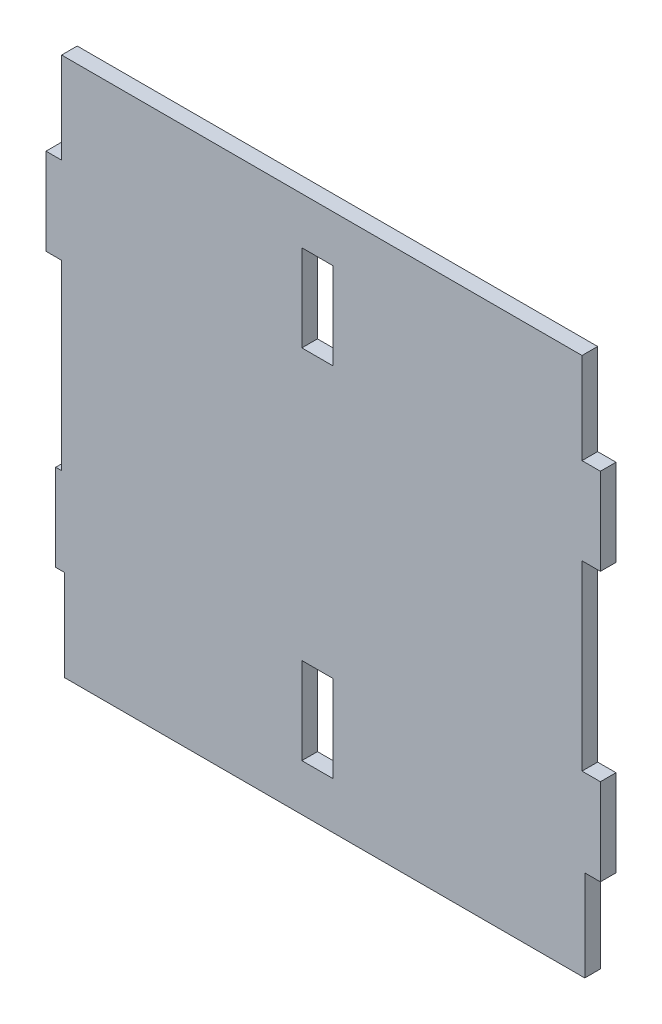
SolidWorks part; units mm, degrees
ref_plane "Front Plane" through (0, 0, 0) normal (0, 0, 1) x (1, 0, 0)
ref_plane "Top Plane" through (0, 0, 0) normal (0, 1, 0) x (1, 0, 0)
ref_plane "Right Plane" through (0, 0, 0) normal (1, 0, 0) x (0, 0, -1)
sketch "Sketch1" plane through (0, 0, 0) normal (0, 0, 1) x (1, 0, 0)
  line L0 (0, 0) -> (0, -105)
  line L6 (0, -205) -> (0, -415)
  line L7 (-18, -105) -> (0, -105)
  line L8 (-18, -105) -> (-18, -205)
  line L13 (-18, -205) -> (0, -205)
  line L21 (603.1762, -619.9919) -> (603.1762, -515)
  line L25 (-6.7801, -415) -> (0, -415)
  line L26 (-6.7801, -515) -> (-6.7801, -415)
  line L27 (-6.7801, -515) -> (3.1762, -514.9919)
  line L28 (3.1762, -619.9919) -> (603.1762, -619.9919)
  line L29 (3.1762, -619.9919) -> (3.1762, -514.9919)
  line L30 (621.1762, -105) -> (600, -105)
  line L31 (621.1762, -105) -> (621.1762, -205)
  line L32 (621.1762, -205) -> (600, -205)
  line L33 (621.1762, -415) -> (600, -415)
  line L34 (621.1762, -515) -> (621.1762, -415)
  line L35 (621.1762, -515) -> (603.1762, -515)
  line L36 (600, 0) -> (600, -105)
  line L37 (600, -205) -> (600, -415)
  line L39 (321.1762, -105) -> (321.1762, -205)
  line L41 (321.1762, -105) -> (282, -105)
  line L42 (321.1762, -105) -> (321.1762, -205)
  line L43 (321.1762, -205) -> (282, -205)
  line L47 (282, -105) -> (282, -205)
  line L49 (600, 0) -> (0, 0)
  line L50 (600, -310) -> (0, -310) construction
  line L51 (321.1762, -205) -> (300, -205) [skipped]
  line L52 (321.1762, -105) -> (300, -105) [skipped]
  line L53 (321.1762, -515) -> (321.1762, -415)
  line L54 (321.1762, -415) -> (282, -415)
  line L55 (282, -515) -> (282, -415)
  line L56 (321.1762, -515) -> (282, -515)
  point P2 (0, -91.1017)
  point P15 (600, -91.1017)
  point P27 (600, -368.8983)
  point P28 (0, -368.8983)
  point P44 (300, -415)
  point P59 (313.2707, -515)
  dimension "D1" = 100
  dimension "D2" = 100
  dimension "D3" = 105
  dimension "D4" = 620
  dimension "D5" = 18
  dimension "D6" = 18
  dimension "D7" = 2
  dimension "D8" = 100
  dimension "D9" = 210
  dimension "D10" = 105
  dimension "D11" = 600
  dimension "D12" = 600
  dimension "D13" = 100
  dimension "D14" = 39.1762
  dimension "D15" = 39.1762
  dimension "D16" = 100
  dimension "D17" = 39.1762
  dimension "D18" = 100
  dimension "D19" = 39.1762
extrude "Boss-Extrude3" add sketch "Sketch1" along normal blind 18 contours L49 L36 L30 L31 L32 L37 L33 L34 L35 L21 L28 L29 L27 L26 L25 L6 L13 L8 L7 L0
sketch "Sketch2" plane through (0, 0, 0) normal (0, 0, -1) x (-1, 0, 0)
  line L3 (-312.9722, -53.941) -> (-276.9722, -53.941)
  line L4 (-276.9722, -53.941) -> (-276.9722, -153.941)
  line L5 (-276.9722, -153.941) -> (-312.9722, -153.941)
  line L6 (-312.9722, -53.941) -> (-312.9722, -153.941)
  line L10 (-312.9722, -566.059) -> (-312.9722, -466.059)
  line L11 (-276.9722, -466.059) -> (-312.9722, -466.059)
  line L12 (-276.9722, -566.059) -> (-276.9722, -466.059)
  line L13 (-312.9722, -566.059) -> (-276.9722, -566.059)
  point P11 (-294.9722, -153.941)
  point P12 (-294.9722, -53.941)
  point P22 (-294.9722, -566.059)
  point P23 (-294.9722, -466.059)
  dimension "D1" = 18
  dimension "D2" = 100
extrude "Cut-Extrude1" cut sketch "Sketch2" against normal through all both and the other way through all contours L5 L6 L3 L4 | L10 L11 L12 L13
